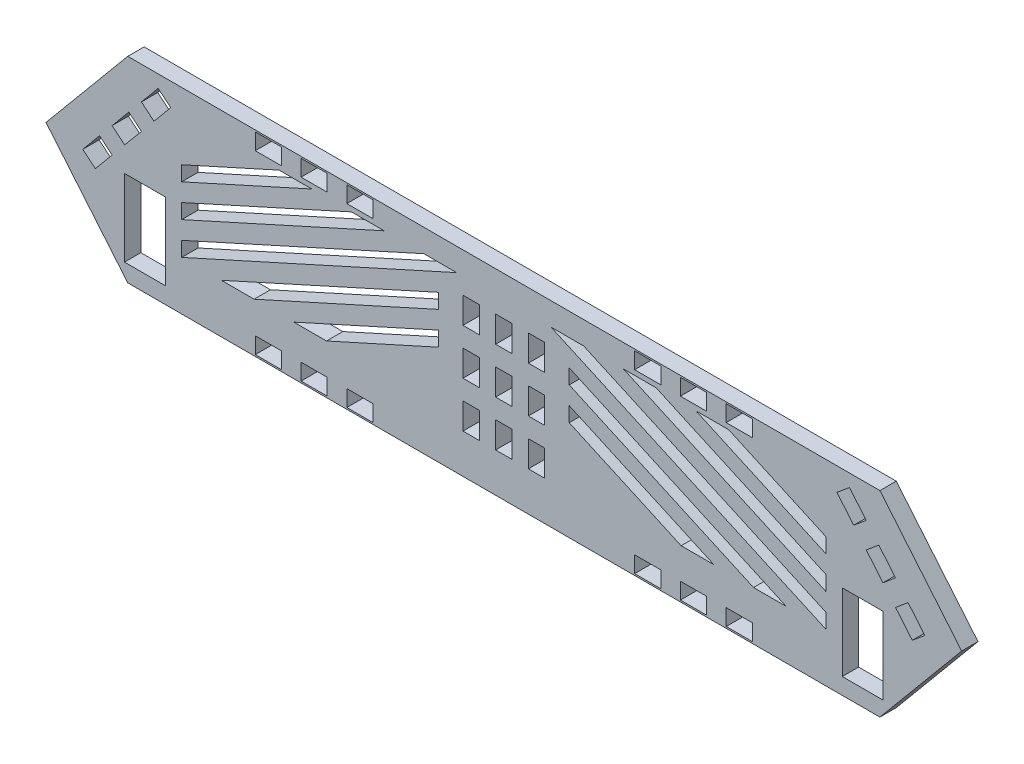
SolidWorks part; units mm, degrees
ref_plane "前视基准面" through (0, 0, 0) normal (0, 0, 1) x (1, 0, 0)
ref_plane "上视基准面" through (0, 0, 0) normal (0, 1, 0) x (1, 0, 0)
ref_plane "右视基准面" through (0, 0, 0) normal (1, 0, 0) x (0, 0, -1)
sketch "草图1" plane through (0, 0, 0) normal (0, 0, 1) x (1, 0, 0)
  line L0 (-140, 0) -> (140, 0) construction
  line L1 (140, 0) -> (115, -30)
  line L2 (115, -30) -> (-115, -30)
  line L3 (-115, -30) -> (-140, 0)
  line L4 (0, 30) -> (0, -30) construction
  line L5 (-127.5, -15) -> (127.5, -15) construction
  line L6 (-127.5, 15) -> (127.5, 15) construction
  line L7 (-115, 30) -> (-140, 0)
  line L8 (115, 30) -> (-115, 30)
  line L9 (140, 0) -> (115, 30)
  line L10 (-127.5, 15) -> (-127.5, -15) construction
  line L11 (127.5, 15) -> (127.5, -15) construction
  line L12 (-115, 30) -> (-115, -30) construction
  line L13 (115, 30) -> (115, -30) construction
  line L14 (-125.4351, 2.4779) -> (-114.1181, 16.0583) construction
  line L15 (-105.7009, 26.1589) -> (-110.8224, 20.0131)
  line L16 (-105.7009, 26.1589) -> (-101.8598, 22.958)
  line L17 (-110.8224, 20.0131) -> (-106.9813, 16.8122)
  line L18 (-101.8598, 22.958) -> (-106.9813, 16.8122)
  line L19 (-114.6635, 15.4038) -> (-119.785, 9.258)
  line L20 (-114.6635, 15.4038) -> (-110.8224, 12.2029)
  line L21 (-119.785, 9.258) -> (-115.9439, 6.0571)
  line L22 (-110.8224, 12.2029) -> (-115.9439, 6.0571)
  line L23 (-123.6261, 4.6487) -> (-128.7476, -1.4971)
  line L24 (-123.6261, 4.6487) -> (-119.785, 1.4478)
  line L25 (-128.7476, -1.4971) -> (-124.9065, -4.698)
  line L26 (-119.785, 1.4478) -> (-124.9065, -4.698)
  line L27 (-98.5, -0.4715) -> (-46.5795, 23)
  line L28 (-103.5, -1.5) -> (-116, -1.5)
  line L29 (-103.5, -1.5) -> (-103.5, -25)
  line L30 (-103.5, -25) -> (-116, -25)
  line L31 (-116, -1.5) -> (-116, -25)
  line L32 (-109.75, -25) -> (-109.75, -1.5) construction
  line L33 (-103.5, -13.25) -> (-116, -13.25) construction
  line L34 (-2.5, 4) -> (2.5, 4)
  line L35 (-2.5, 4) -> (-2.5, -4)
  line L36 (-2.5, -4) -> (2.5, -4)
  line L37 (2.5, 4) -> (2.5, -4)
  line L38 (0, -4) -> (0, 4) construction
  line L39 (-2.5, 0) -> (2.5, 0) construction
  line L40 (-2.5, 18) -> (2.5, 18)
  line L41 (-2.5, 18) -> (-2.5, 10)
  line L42 (-2.5, 10) -> (2.5, 10)
  line L43 (2.5, 18) -> (2.5, 10)
  line L44 (0, 10) -> (0, 18) construction
  line L45 (-2.5, 14) -> (2.5, 14) construction
  line L46 (-2.5, -10) -> (2.5, -10)
  line L47 (-2.5, -10) -> (-2.5, -18)
  line L48 (-2.5, -18) -> (2.5, -18)
  line L49 (2.5, -10) -> (2.5, -18)
  line L50 (0, -18) -> (0, -10) construction
  line L51 (-2.5, -14) -> (2.5, -14) construction
  line L52 (-46.5795, 23) -> (-36.5795, 23)
  line L53 (-36.5795, 23) -> (-98.5, -4.9922)
  line L54 (-98.5, -4.9922) -> (-98.5, -3)
  line L55 (-98.5, -10.4793) -> (-24.4415, 23)
  line L56 (-24.4415, 23) -> (-14.4415, 23)
  line L57 (-14.4415, 23) -> (-98.5, -15)
  line L58 (-98.5, -0.4715) -> (-98.5, -3)
  line L59 (-20, 15) -> (-86.362, -15)
  line L60 (-86.362, -15) -> (-76.362, -15)
  line L61 (-76.362, -15) -> (-20, 10.4793)
  line L62 (-98.5, -10.932) -> (-98.5, -19.7216) construction
  line L63 (-20, 14.068) -> (-20, 1.568) construction
  line L64 (-20, 10.4793) -> (-20, 15)
  line L65 (-98.5, -15) -> (-98.5, -10.4793)
  line L66 (-20, 4.9922) -> (-64.224, -15)
  line L67 (-64.224, -15) -> (-54.224, -15)
  line L68 (-54.224, -15) -> (-20, 0.4715)
  line L69 (-20, 0.4715) -> (-20, 4.9922)
  line L70 (-30.0679, 23) -> (-18.0659, 23) construction
  line L71 (-58.7175, 23) -> (-68.7175, 23)
  line L72 (-68.7175, 23) -> (-98.5, 9.5363)
  line L73 (-98.5, 9.5363) -> (-98.5, 5.0157)
  line L74 (-98.5, 5.0157) -> (-58.7175, 23)
  line L75 (103.5, -13.25) -> (116, -13.25) construction
  line L76 (109.75, -25) -> (109.75, -1.5) construction
  line L77 (115, 30) -> (115, -30) construction
  line L78 (127.5, 15) -> (127.5, -15) construction
  line L79 (98.5, 5.0157) -> (58.7175, 23)
  line L80 (98.5, 9.5363) -> (98.5, 5.0157)
  line L81 (68.7175, 23) -> (98.5, 9.5363)
  line L82 (58.7175, 23) -> (68.7175, 23)
  line L83 (20, 0.4715) -> (20, 4.9922)
  line L84 (54.224, -15) -> (20, 0.4715)
  line L85 (64.224, -15) -> (54.224, -15)
  line L86 (20, 4.9922) -> (64.224, -15)
  line L87 (98.5, -15) -> (98.5, -10.4793)
  line L88 (20, 10.4793) -> (20, 15)
  line L89 (76.362, -15) -> (20, 10.4793)
  line L90 (86.362, -15) -> (76.362, -15)
  line L91 (20, 15) -> (86.362, -15)
  line L92 (98.5, -0.4715) -> (98.5, -3)
  line L93 (14.4415, 23) -> (98.5, -15)
  line L94 (24.4415, 23) -> (14.4415, 23)
  line L95 (98.5, -10.4793) -> (24.4415, 23)
  line L96 (98.5, -4.9922) -> (98.5, -3)
  line L97 (36.5795, 23) -> (98.5, -4.9922)
  line L98 (46.5795, 23) -> (36.5795, 23)
  line L99 (116, -1.5) -> (116, -25)
  line L100 (103.5, -25) -> (116, -25)
  line L101 (103.5, -1.5) -> (103.5, -25)
  line L102 (103.5, -1.5) -> (116, -1.5)
  line L103 (98.5, -0.4715) -> (46.5795, 23)
  line L104 (119.785, 1.4478) -> (124.9065, -4.698)
  line L105 (128.7476, -1.4971) -> (124.9065, -4.698)
  line L106 (123.6261, 4.6487) -> (119.785, 1.4478)
  line L107 (123.6261, 4.6487) -> (128.7476, -1.4971)
  line L108 (110.8224, 12.2029) -> (115.9439, 6.0571)
  line L109 (119.785, 9.258) -> (115.9439, 6.0571)
  line L110 (114.6635, 15.4038) -> (110.8224, 12.2029)
  line L111 (114.6635, 15.4038) -> (119.785, 9.258)
  line L112 (101.8598, 22.958) -> (106.9813, 16.8122)
  line L113 (110.8224, 20.0131) -> (106.9813, 16.8122)
  line L114 (105.7009, 26.1589) -> (101.8598, 22.958)
  line L115 (105.7009, 26.1589) -> (110.8224, 20.0131)
  line L116 (-12.5, 4) -> (-7.5, 4)
  line L117 (-12.5, 4) -> (-12.5, -4)
  line L118 (-12.5, -4) -> (-7.5, -4)
  line L119 (-7.5, 4) -> (-7.5, -4)
  line L120 (-10, -4) -> (-10, 4) construction
  line L121 (-12.5, 0) -> (-7.5, 0) construction
  line L122 (-12.5, 18) -> (-7.5, 18)
  line L123 (-12.5, 18) -> (-12.5, 10)
  line L124 (-12.5, 10) -> (-7.5, 10)
  line L125 (-7.5, 18) -> (-7.5, 10)
  line L126 (-10, 10) -> (-10, 18) construction
  line L127 (-12.5, 14) -> (-7.5, 14) construction
  line L128 (-12.5, -10) -> (-7.5, -10)
  line L129 (-12.5, -10) -> (-12.5, -18)
  line L130 (-12.5, -18) -> (-7.5, -18)
  line L131 (-7.5, -10) -> (-7.5, -18)
  line L132 (-10, -18) -> (-10, -10) construction
  line L133 (-12.5, -14) -> (-7.5, -14) construction
  line L134 (12.5, -14) -> (7.5, -14) construction
  line L135 (10, -18) -> (10, -10) construction
  line L136 (12.5, 14) -> (7.5, 14) construction
  line L137 (10, 10) -> (10, 18) construction
  line L138 (12.5, 0) -> (7.5, 0) construction
  line L139 (10, -4) -> (10, 4) construction
  line L140 (7.5, -10) -> (7.5, -18)
  line L141 (12.5, -18) -> (7.5, -18)
  line L142 (12.5, -10) -> (12.5, -18)
  line L143 (12.5, -10) -> (7.5, -10)
  line L144 (7.5, 18) -> (7.5, 10)
  line L145 (12.5, 10) -> (7.5, 10)
  line L146 (12.5, 18) -> (12.5, 10)
  line L147 (12.5, 18) -> (7.5, 18)
  line L148 (7.5, 4) -> (7.5, -4)
  line L149 (12.5, -4) -> (7.5, -4)
  line L150 (12.5, 4) -> (12.5, -4)
  line L151 (12.5, 4) -> (7.5, 4)
  line L152 (-62, 29.5) -> (-54, 29.5)
  line L153 (-76, 29.5) -> (-68, 29.5)
  line L154 (-76, 29.5) -> (-76, 24.5)
  line L155 (-76, 24.5) -> (-68, 24.5)
  line L156 (-68, 29.5) -> (-68, 24.5)
  line L157 (-72, 24.5) -> (-72, 29.5) construction
  line L158 (-76, 27) -> (-68, 27) construction
  line L159 (-62, 29.5) -> (-62, 24.5)
  line L160 (-62, 24.5) -> (-54, 24.5)
  line L161 (-54, 29.5) -> (-54, 24.5)
  line L162 (-58, 24.5) -> (-58, 29.5) construction
  line L163 (-62, 27) -> (-54, 27) construction
  line L164 (-48, 29.5) -> (-40, 29.5)
  line L165 (-48, 29.5) -> (-48, 24.5)
  line L166 (-48, 24.5) -> (-40, 24.5)
  line L167 (-40, 29.5) -> (-40, 24.5)
  line L168 (-44, 24.5) -> (-44, 29.5) construction
  line L169 (-48, 27) -> (-40, 27) construction
  line L170 (-68, 29.5) -> (-62, 29.5) construction
  line L171 (-54, 29.5) -> (-48, 29.5) construction
  line L172 (72, -24.5) -> (72, -29.5) construction
  line L173 (76, -27) -> (68, -27) construction
  line L174 (58, -24.5) -> (58, -29.5) construction
  line L175 (62, -27) -> (54, -27) construction
  line L176 (44, -24.5) -> (44, -29.5) construction
  line L177 (48, -27) -> (40, -27) construction
  line L178 (68, -29.5) -> (62, -29.5) construction
  line L179 (54, -29.5) -> (48, -29.5) construction
  line L180 (-54, -29.5) -> (-48, -29.5) construction
  line L181 (-68, -29.5) -> (-62, -29.5) construction
  line L182 (-48, -27) -> (-40, -27) construction
  line L183 (-44, -24.5) -> (-44, -29.5) construction
  line L184 (-62, -27) -> (-54, -27) construction
  line L185 (-58, -24.5) -> (-58, -29.5) construction
  line L186 (-76, -27) -> (-68, -27) construction
  line L187 (-72, -24.5) -> (-72, -29.5) construction
  line L188 (62, -29.5) -> (54, -29.5)
  line L189 (76, -29.5) -> (68, -29.5)
  line L190 (76, -29.5) -> (76, -24.5)
  line L191 (76, -24.5) -> (68, -24.5)
  line L192 (54, 29.5) -> (48, 29.5) construction
  line L193 (68, 29.5) -> (62, 29.5) construction
  line L194 (48, 27) -> (40, 27) construction
  line L195 (44, 24.5) -> (44, 29.5) construction
  line L196 (62, 27) -> (54, 27) construction
  line L197 (58, 24.5) -> (58, 29.5) construction
  line L198 (76, 27) -> (68, 27) construction
  line L199 (72, 24.5) -> (72, 29.5) construction
  line L200 (40, 29.5) -> (40, 24.5)
  line L201 (48, 24.5) -> (40, 24.5)
  line L202 (48, 29.5) -> (48, 24.5)
  line L203 (48, 29.5) -> (40, 29.5)
  line L204 (54, 29.5) -> (54, 24.5)
  line L205 (62, 24.5) -> (54, 24.5)
  line L206 (62, 29.5) -> (62, 24.5)
  line L207 (68, 29.5) -> (68, 24.5)
  line L208 (76, 24.5) -> (68, 24.5)
  line L209 (76, 29.5) -> (76, 24.5)
  line L210 (76, 29.5) -> (68, 29.5)
  line L211 (62, 29.5) -> (54, 29.5)
  line L212 (68, -29.5) -> (68, -24.5)
  line L213 (62, -29.5) -> (62, -24.5)
  line L214 (62, -24.5) -> (54, -24.5)
  line L215 (54, -29.5) -> (54, -24.5)
  line L216 (48, -29.5) -> (40, -29.5)
  line L217 (48, -29.5) -> (48, -24.5)
  line L218 (48, -24.5) -> (40, -24.5)
  line L219 (40, -29.5) -> (40, -24.5)
  line L220 (-40, -29.5) -> (-40, -24.5)
  line L221 (-48, -24.5) -> (-40, -24.5)
  line L222 (-48, -29.5) -> (-48, -24.5)
  line L223 (-48, -29.5) -> (-40, -29.5)
  line L224 (-54, -29.5) -> (-54, -24.5)
  line L225 (-62, -24.5) -> (-54, -24.5)
  line L226 (-62, -29.5) -> (-62, -24.5)
  line L227 (-68, -29.5) -> (-68, -24.5)
  line L228 (-76, -24.5) -> (-68, -24.5)
  line L229 (-76, -29.5) -> (-76, -24.5)
  line L230 (-76, -29.5) -> (-68, -29.5)
  line L231 (-62, -29.5) -> (-54, -29.5)
  point P3 (0, 0)
  point P5 (0, -30)
  point P13 (0, 0)
  point P16 (-127.5, 0)
  point P18 (-102.5, 30)
  point P19 (-115, 15)
  point P32 (-109.75, -13.25)
  point P38 (0, 0)
  point P42 (0, 14)
  point P46 (0, -14)
  point P74 (-72, 27)
  point P118 (109.75, -13.25)
  point P124 (115, 15)
  point P125 (102.5, 30)
  point P126 (127.5, 0)
  point P130 (-58, 27)
  point P139 (-44, 27)
  point P141 (-10, 0)
  point P143 (-10, 0)
  point P147 (-10, 14)
  point P151 (-10, -14)
  point P200 (10, -14)
  point P201 (10, 14)
  point P202 (10, 0)
  point P265 (44, 27)
  point P266 (58, 27)
  point P267 (72, 27)
  point P295 (72, -27)
  point P296 (58, -27)
  point P297 (44, -27)
  point P298 (-44, -27)
  point P299 (-58, -27)
  point P300 (-72, -27)
  dimension "D4" = 5
  dimension "D5" = 20
  dimension "D6" = 8
  dimension "D7" = 8
  dimension "D22" = 7
  dimension "D1" = 280
  dimension "D2" = 230
  dimension "D3" = 30
  dimension "D8" = 5
  dimension "D9" = 8
  dimension "D10" = 5
  dimension "D11" = 5
  dimension "D12" = 6
  dimension "D13" = 6
  dimension "D14" = 8
  dimension "D15" = 5
  dimension "D16" = 8
  dimension "D17" = 5
  dimension "D18" = 6
  dimension "D19" = 8
  dimension "D20" = 5
  dimension "D21" = 6
  dimension "D23" = 5
  dimension "D24" = 12.5
  dimension "D25" = 23.5
  dimension "D26" = 10
  dimension "D27" = 8
  dimension "D28" = 5
  dimension "D29" = 1
  dimension "D30" = 8
  dimension "D31" = 5
  dimension "D32" = 5
  dimension "D33" = 5
  dimension "D34" = 5
  dimension "D35" = 5
  dimension "D36" = 6
  dimension "D37" = 8
  dimension "D38" = 5
  dimension "D39" = 6
  dimension "D40" = 10
  dimension "D41" = 8
  dimension "D42" = 5
  dimension "D43" = 6
  dimension "D44" = 3
  dimension "D45" = 5
  dimension "D49" = 40
extrude "凸台-拉伸1" add sketch "草图1" along normal blind 5
